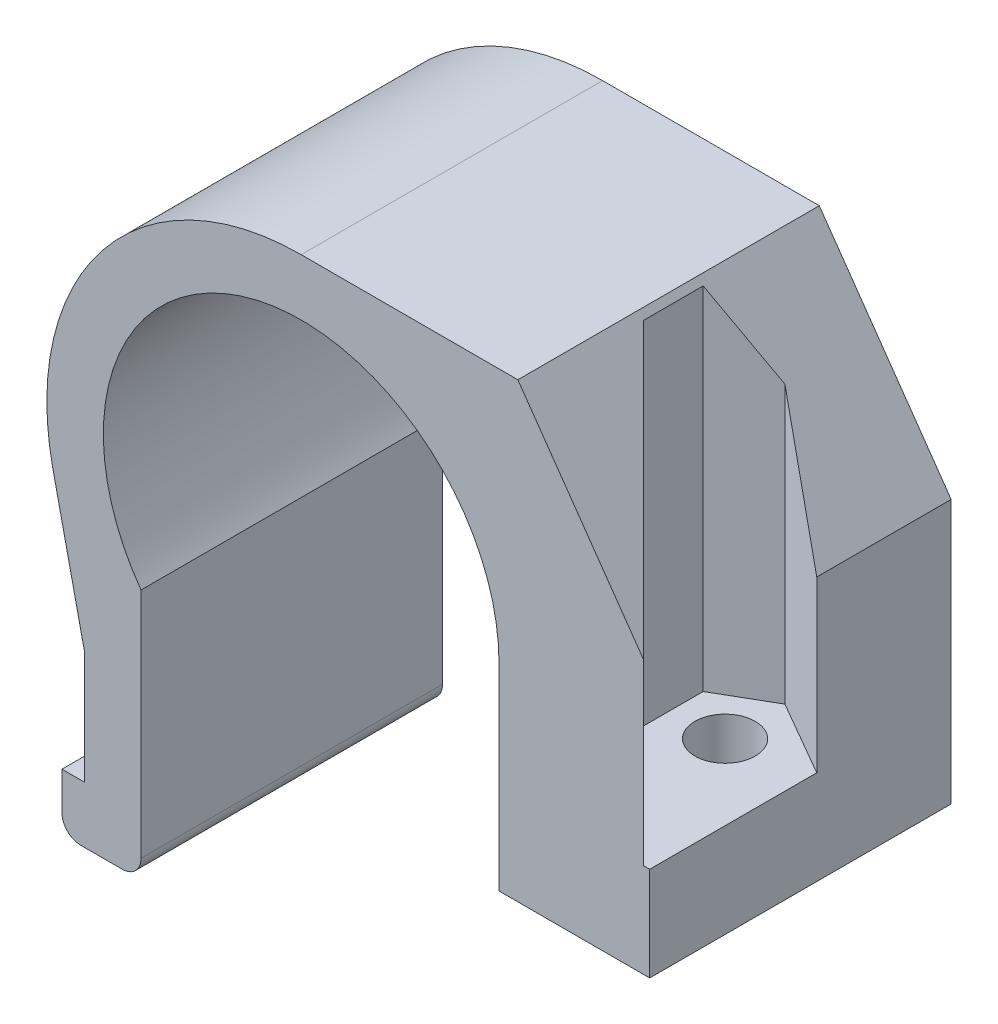
SolidWorks part; units mm, degrees
ref_plane "Front Plane" through (0, 0, 0) normal (0, 0, 1) x (1, 0, 0)
ref_plane "Top Plane" through (0, 0, 0) normal (0, 1, 0) x (1, 0, 0)
ref_plane "Right Plane" through (0, 0, 0) normal (1, 0, 0) x (0, 0, -1)
sketch "Sketch1" plane through (0, 0, 0) normal (0, 0, 1) x (1, 0, 0)
  line L0 (-23.622, -10.5) -> (30.4823, -10.5) construction
  line L1 (-23.622, -16.5) -> (30.4823, -16.5) construction
  line L2 (10.5, 0) -> (10.5, -10.5)
  line L3 (10.5, -10.5) -> (18.5, -10.5)
  line L4 (0, 13.5) -> (18.5, 13.5)
  line L5 (-8.5, -6.1644) -> (-8.5, -19.5)
  line L6 (-8.5, -19.5) -> (-11.6978, -19.5)
  line L7 (-12.6978, -16.5) -> (-11.5, -16.5)
  line L8 (-11.5, -16.5) -> (-11.5, -10.5)
  line L9 (-12.6978, -16.5) -> (-12.6978, -18.5)
  line L10 (18.5, 13.5) -> (18.5, -10.5)
  line L12 (-11.5, -10.5) -> (-13.18, -2.9219)
  arc A0 (-11.6978, -19.5) -> (-12.6978, -18.5) centre (-11.6978, -18.5) cw
  arc A4 (10.5, 0) -> (-8.5, -6.1644) centre (0, 0) ccw
  arc A5 (0, 13.5) -> (-13.18, -2.9219) centre (0, 0) ccw
  dimension "D1" = 3
  dimension "D4" = 3
  dimension "D5" = 1
  dimension "D6" = 21
  dimension "D7" = 3
  dimension "D3" = 8
  dimension "D2" = 6
extrude "Boss-Extrude1" add sketch "Sketch1" along normal blind 16
chamfer "Chamfer1" distance 10 distance2 7 1 edges at (18.5, 13.5, 8)
sketch "Sketch2" plane through (0, -10.5, 0) normal (0, -1, 0) x (1, 0, 0)
  line L0 (14.5, 16) -> (14.5, 0) construction
  line L1 (10.5, 16) -> (18.5, 16) construction
  line L2 (10.5, 0) -> (18.5, 0) construction
  line L3 (18.5, 8) -> (14.5, 8) construction
  line L5 (18.5, 16) -> (18.5, 0) construction
  circle A0 centre (14.5, 8) radius 1.6
  dimension "D1" = 3.2
extrude "Cut-Extrude1" cut sketch "Sketch2" against normal through all
sketch "Sketch3" plane through (0, -10.5, 0) normal (0, -1, 0) x (1, 0, 0)
  line L0 (17.25, 6.4123) -> (19.6091, 7.7743)
  line L1 (14.5, 11.1754) -> (11.75, 9.5877) construction
  line L2 (11.75, 9.5877) -> (11.75, 6.4123)
  line L3 (11.75, 6.4123) -> (14.5, 4.8246)
  line L4 (14.5, 4.8246) -> (17.25, 6.4123)
  line L5 (17.25, 6.4123) -> (17.25, 9.5877) construction
  line L6 (17.25, 9.5877) -> (14.5, 11.1754) construction
  line L8 (19.6091, 7.7743) -> (19.6091, 17.4468)
  line L10 (19.6091, 17.4468) -> (11.75, 9.5877)
  circle A0 centre (14.5, 8) radius 2.75 construction
  dimension "D1" = 5.5
  dimension "D2" = 45
extrude "Cut-Extrude2" cut sketch "Sketch3" against normal through all from offset 5 offset against normal yes
fillet "Fillet1" radius 1 1 edges at (-8.5, -19.5, 8)
